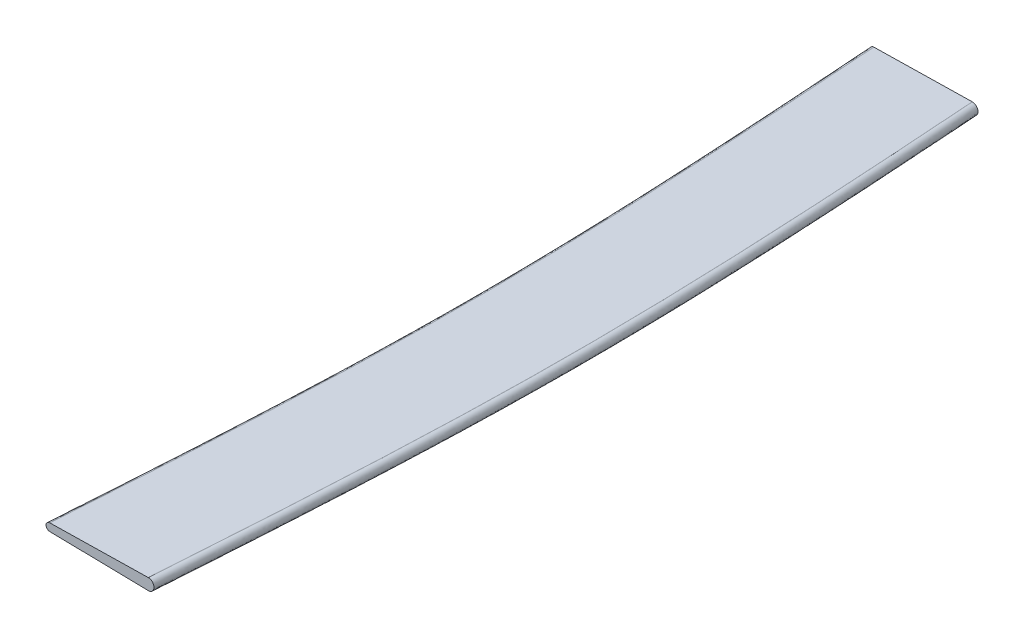
SolidWorks part; units mm, degrees
material "Hexcel AS4C (3000 Filaments)"
ref_plane "Front Plane" through (0, 0, 0) normal (0, 0, 1) x (1, 0, 0)
ref_plane "Top Plane" through (0, 0, 0) normal (0, 1, 0) x (1, 0, 0)
ref_plane "Right Plane" through (0, 0, 0) normal (1, 0, 0) x (0, 0, -1)
sketch "Sketch1" plane through (0, 0, 0) normal (0, 0, 1) x (1, 0, 0)
  line L0 (-65, 0) -> (65, 0) construction
  line L1 (-65, 5) -> (64.9391, 7.4988)
  line L2 (-65, -5) -> (64.9391, -7.4988)
  arc A0 (65.1056, -7.4993) -> (65.1056, 7.4993) centre (65, 0) ccw
  arc A1 (-65, 5) -> (-65, -5) centre (-65, 0) ccw
  arc A2 (64.9391, 7.4988) -> (65.1056, 7.4993) centre (65.0352, 2.4998) cw
  arc A3 (64.9391, -7.4988) -> (65.1056, -7.4993) centre (65.0352, -2.4998) ccw
  point P3 (0, 0)
  point P8 (65, 7.5)
  point P11 (65, -7.5)
  dimension "D2" = 15
  dimension "D3" = 10
  dimension "D4" = 5
  dimension "D5" = 5
  dimension "D1" = 130
sketch "Sketch2" plane through (0, 0, 0) normal (0, 1, 0) x (1, 0, 0)
  line L0 (-65, 0) -> (64.9391, 0) construction
  line L1 (-121.9843, -1945.3095) -> (73.3338, 847.8699) construction
  line L2 (73.2442, -846.5886) -> (-122.0739, 1946.5908) construction
  spline S0 degree 3 poles (-24.4148, 550) (8.1383, 84.4701) (8.1383, -84.4701) (-24.4148, -550) knots 0 0 0 0 1 1 1 1
  dimension "D3" = 1400
  dimension "D4" = 1400
  dimension "D1" = 550
  dimension "D2" = 550
  dimension "D5" = 94
  dimension "D6" = 94
sweep "Sweep2" add profiles "Sketch1" path "Sketch2"
sketch "Sketch3" plane through (0, 0, 0) normal (0, 1, 0) x (1, 0, 0)
  line L0 (-94.2442, 545.117) -> (61.7826, 545.117) construction
  line L1 (-94.2442, -545.117) -> (74.3717, -545.117) construction
  line L2 (-94.2442, 545.117) -> (52.9529, 545.117)
  line L3 (-94.2442, 545.117) -> (-94.2442, 562.6563)
  line L4 (-94.2442, 562.6563) -> (52.9529, 562.6563)
  line L5 (52.9529, 545.117) -> (52.9529, 562.6563)
  line L7 (-94.2442, -545.117) -> (50.3298, -545.117)
  line L8 (-94.2442, -545.117) -> (-94.2442, -565.3705)
  line L9 (-94.2442, -565.3705) -> (50.3298, -565.3705)
  line L10 (50.3298, -545.117) -> (50.3298, -565.3705)
extrude "Cut-Extrude1" cut sketch "Sketch3" against normal mid plane 70
